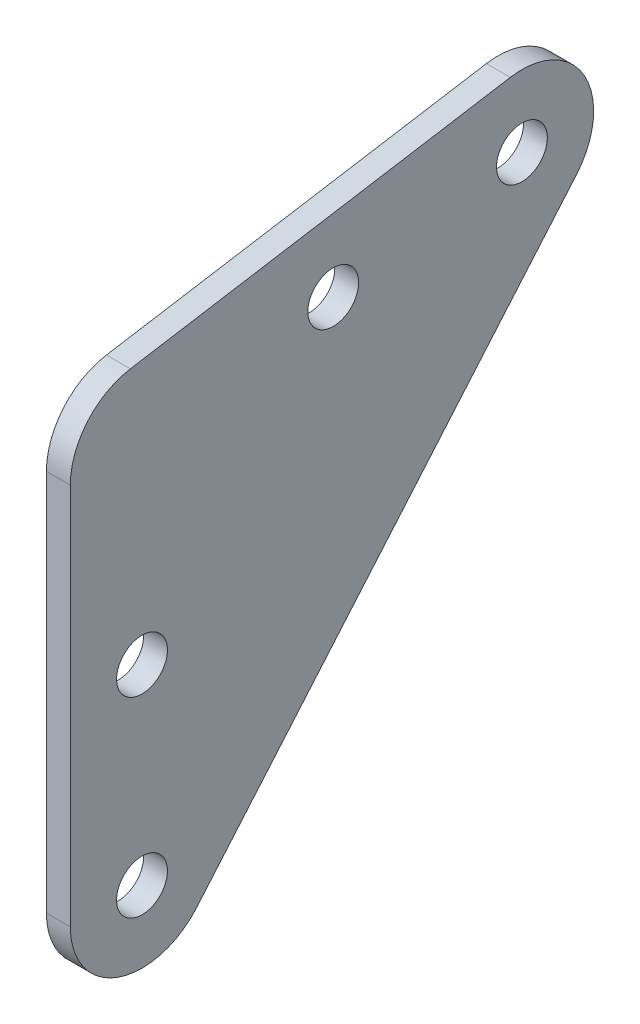
SolidWorks part; units mm, degrees
ref_plane "Front Plane" through (0, 0, 0) normal (0, 0, 1) x (1, 0, 0)
ref_plane "Top Plane" through (0, 0, 0) normal (0, 1, 0) x (1, 0, 0)
ref_plane "Right Plane" through (0, 0, 0) normal (1, 0, 0) x (0, 0, -1)
sketch "Sketch1" plane through (0, 0, 0) normal (1, 0, 0) x (0, 0, -1)
  line L0 (-1304.62, 323.5779) -> (-1279.5563, 327.6971) construction
  line L1 (-1338.0003, 318.0919) -> (-1304.62, 323.5779) construction
  line L2 (-1338.0003, 284.6046) -> (-1338.0003, 318.0919) construction
  line L3 (-1321.232, 253.0191) -> (-1270.7683, 312.1127) construction
  line L4 (-1338.0003, 259.2046) -> (-1338.0003, 284.6046) construction
  line L5 (-1304.62, 323.5779) -> (-1279.5563, 327.6971)
  line L6 (-1338.0003, 318.0919) -> (-1304.62, 323.5779)
  line L7 (-1338.0003, 284.6046) -> (-1338.0003, 318.0919)
  line L8 (-1321.232, 253.0191) -> (-1270.7683, 312.1127)
  line L9 (-1338.0003, 259.2046) -> (-1338.0003, 284.6046)
  circle A0 centre (-1278.0116, 318.2982) radius 9.525 construction
  circle A1 centre (-1328.4753, 259.2046) radius 9.525 construction
  arc A2 (-1270.7683, 312.1127) -> (-1279.5563, 327.6971) centre (-1278.0116, 318.2982) ccw
  arc A3 (-1338.0003, 259.2046) -> (-1321.232, 253.0191) centre (-1328.4753, 259.2046) ccw
extrude "Boss-Extrude1" add sketch "Sketch1" against normal up to vertex from vertex
fillet "Fillet1" radius 9.525 1 edges at (94.4563, 318.0919, 1338.0003)
hole_wizard "1/4 Clearance Hole1" positions "Sketch2" profile "Sketch3" hole size "1/4" standard "ANSI Inch" end condition through all
sketch "Sketch2" plane through (96.0438, 0, 0) normal (1, 0, 0) x (0, 0, -1)
  point P0 (-1303.0753, 314.179)
  point P3 (-1278.0116, 318.2982)
  point P6 (-1328.4753, 284.6046)
  point P9 (-1328.4753, 259.2046)
sketch "Sketch3" plane through (96.0438, 314.179, 1303.0753) normal (0, 1, 0) x (0, 0, -1)
  line L0 (0, 0) -> (0, 3.175)
  line L1 (0, 3.175) -> (3.3782, 3.175)
  line L2 (3.3782, 3.175) -> (3.3782, 0)
  line L5 (3.3782, 0) -> (0, 0)
  line L11 (0, -6.35) -> (0, 107.95) construction
  dimension "Thru Hole Dia." = 6.7564
  dimension "Thru Hole Depth" = 3.175
